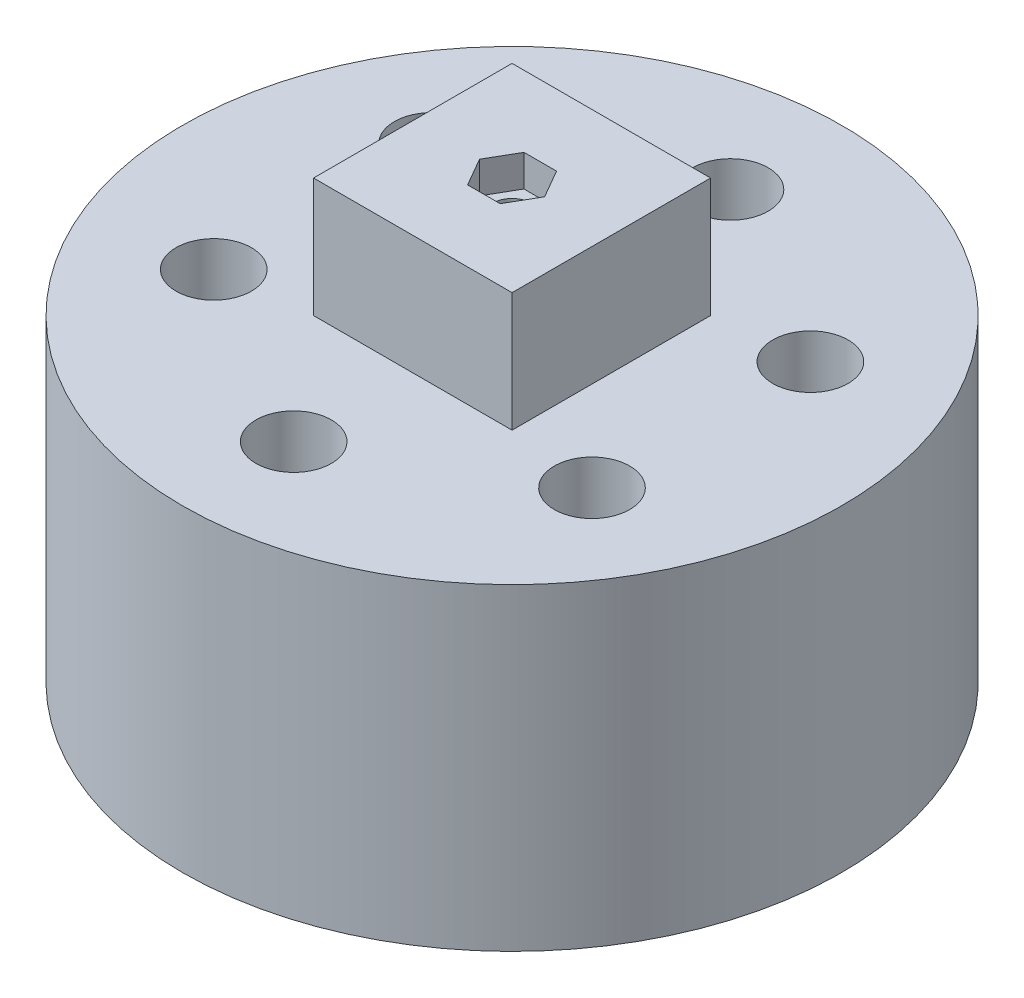
SolidWorks part; units mm, degrees
ref_plane "Ebene vorne" through (0, 0, 0) normal (0, 0, 1) x (1, 0, 0)
ref_plane "Ebene oben" through (0, 0, 0) normal (0, 1, 0) x (1, 0, 0)
ref_plane "Ebene rechts" through (0, 0, 0) normal (1, 0, 0) x (0, 0, -1)
sketch "Sketch1" plane through (0, 0, 0) normal (0, 1, 0) x (1, 0, 0)
  circle A0 centre (0, 0) radius 41.5
  dimension "D1" = 83
extrude "Main Plate" add sketch "Sketch1" along normal blind 40
sketch "Sketch2" plane through (0, 40, 0) normal (0, 1, 0) x (1, 0, 0)
  line L0 (0, 0) -> (0, 41.5) construction
  circle A1 centre (0, 0) radius 41.5 construction
  circle A2 centre (0, 27.5) radius 2.05
  circle A3 centre (23.8157, 13.75) radius 2.05
  circle A4 centre (23.8157, -13.75) radius 2.05
  circle A5 centre (0, -27.5) radius 2.05
  circle A6 centre (-23.8157, -13.75) radius 2.05
  circle A7 centre (-23.8157, 13.75) radius 2.05
  point P20 (0, 0)
  dimension "D1" = 27.5
  dimension "D2" = 4.1
extrude "G27" cut sketch "Sketch2" against normal through all
sketch "Sketch5" plane through (0, 40, 0) normal (0, 1, 0) x (1, 0, 0)
  circle A0 centre (0, 27.5) radius 4.75
  circle A1 centre (23.8157, 13.75) radius 4.75
  circle A2 centre (23.8157, -13.75) radius 4.75
  circle A3 centre (0, -27.5) radius 4.75
  circle A4 centre (-23.8157, -13.75) radius 4.75
  circle A5 centre (-23.8157, 13.75) radius 4.75
  point P15 (0, 0)
  dimension "D1" = 9.5
  dimension "D2" = 6
extrude "G27 Screw Heads" cut sketch "Sketch5" against normal offset from surface (37 mm away) 3 up to face at (-23.8157, 0, -11.7)
sketch "Sketch6" plane through (0, 40, 0) normal (0, 1, 0) x (1, 0, 0)
  line L1 (12.5, -12.5) -> (-12.5, -12.5)
  line L2 (12.5, -12.5) -> (12.5, 12.5)
  line L3 (12.5, 12.5) -> (-12.5, 12.5)
  line L4 (-12.5, -12.5) -> (-12.5, 12.5)
  line L5 (12.5, -12.5) -> (-12.5, 12.5) construction
  line L6 (12.5, 12.5) -> (-12.5, -12.5) construction
  point P0 (0, 0)
  dimension "D1" = 25
  dimension "D2" = 25
extrude "Boss-Extrude1" add sketch "Sketch6" along normal blind 15
sketch "Sketch8" plane through (0, 0, 0) normal (0, -1, 0) x (1, 0, 0)
  circle A0 centre (0, 0) radius 4.5
  dimension "D1" = 9
extrude "Cut-Extrude1" cut sketch "Sketch8" against normal offset from surface (45 mm away) 10 up to face at (0, 55, 0)
sketch "Sketch9" plane through (0, 45, 0) normal (0, -1, 0) x (1, 0, 0)
  circle A0 centre (0, 0) radius 4.5
  circle A1 centre (0, 0) radius 4.5 construction
extrude "Cut-Extrude2" cut sketch "Sketch9" against normal blind 14 draft 45
sketch "Sketch10" plane through (0, 55, 0) normal (0, 1, 0) x (1, 0, 0)
  circle A0 centre (0, 0) radius 2.5
  dimension "D1" = 5
extrude "Cut-Extrude3" cut sketch "Sketch10" against normal through all
sketch "Sketch11" plane through (0, 55, 0) normal (0, 1, 0) x (1, 0, 0)
  line L1 (-4.0992, 0) -> (-2.0496, -3.55)
  line L2 (-2.0496, -3.55) -> (2.0496, -3.55)
  line L3 (2.0496, -3.55) -> (4.0992, 0)
  line L4 (4.0992, 0) -> (2.0496, 3.55)
  line L5 (2.0496, 3.55) -> (-2.0496, 3.55)
  line L6 (-2.0496, 3.55) -> (-4.0992, 0)
  circle A0 centre (0, 0) radius 3.55 construction
  dimension "D1" = 7.1
extrude "Cut-Extrude4" cut sketch "Sketch11" against normal blind 4
